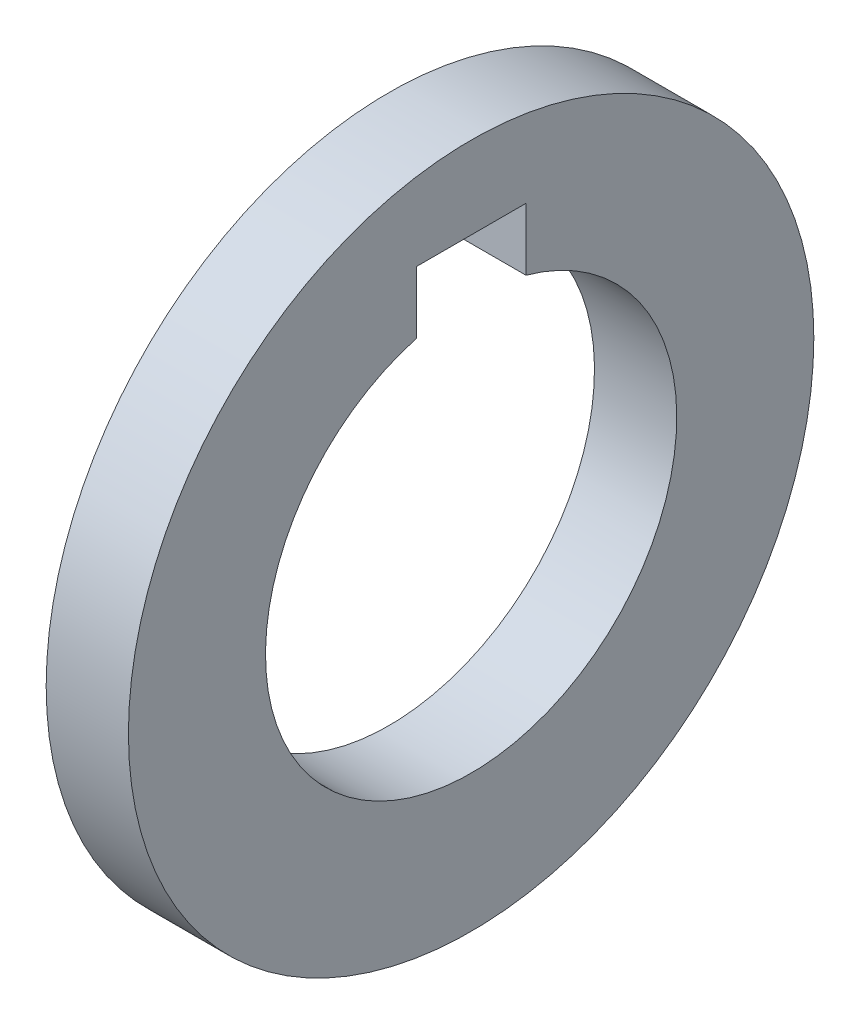
SolidWorks part; units mm, degrees
ref_plane "Front Plane" through (0, 0, 0) normal (0, 0, 1) x (1, 0, 0)
ref_plane "Top Plane" through (0, 0, 0) normal (0, 1, 0) x (1, 0, 0)
ref_plane "Right Plane" through (0, 0, 0) normal (1, 0, 0) x (0, 0, -1)
sketch "Sketch1" plane through (0, 0, 0) normal (1, 0, 0) x (0, 0, -1)
  circle A0 centre (0, 0) radius 12.5
  circle A1 centre (0, 0) radius 7.5
  dimension "D1" = 25
  dimension "D2" = 15
extrude "Boss-Extrude1" add sketch "Sketch1" along normal blind 3
sketch "Sketch2" plane through (0, 0, 0) normal (-1, 0, 0) x (0, 0, 1)
  line L0 (-2, 9.5) -> (-2, 5.5)
  line L1 (-2, 9.5) -> (2, 9.5)
  line L2 (-2, 5.5) -> (2, 5.5)
  line L3 (2, 9.5) -> (2, 5.5)
  line L4 (-2, 9.5) -> (2, 5.5) construction
  line L5 (-2, 5.5) -> (2, 9.5) construction
  line L6 (0, 7.5) -> (0, 0) construction
  circle A0 centre (0, 0) radius 7.5 construction
  point P1 (0, 7.5)
  dimension "D1" = 4
extrude "Cut-Extrude1" cut sketch "Sketch2" against normal blind 10
move or copy body "Body-Move/Copy1" [suppressed] bodies to move or copy 106
